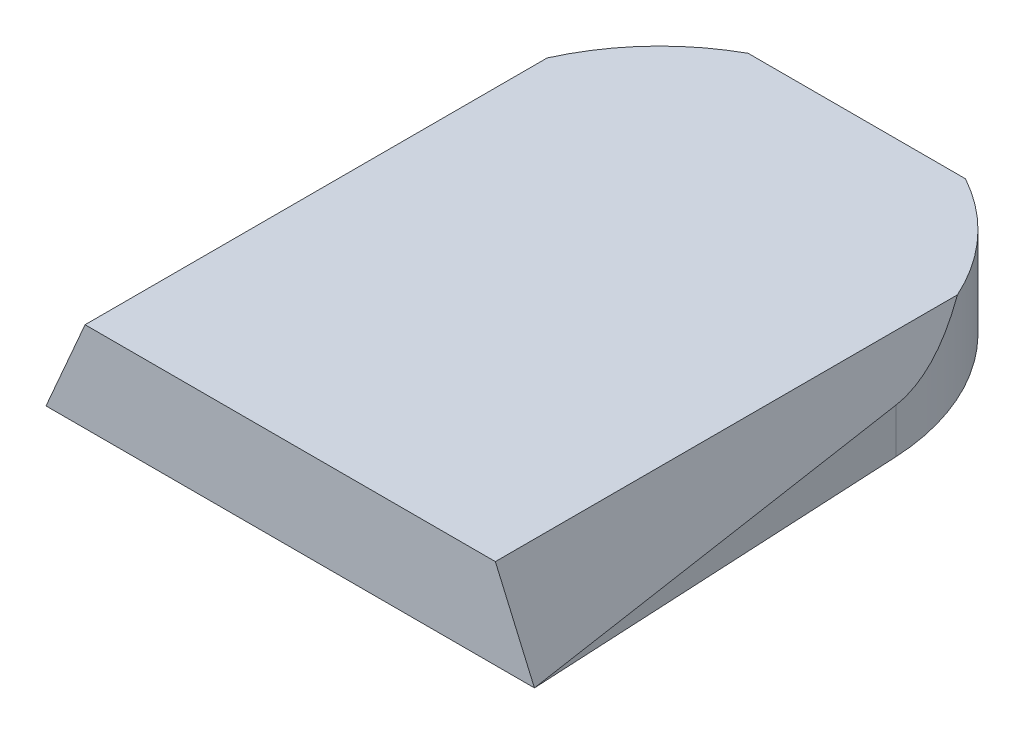
SolidWorks part; units mm, degrees
ref_plane "前视基准面" through (0, 0, 0) normal (0, 0, 1) x (1, 0, 0)
ref_plane "上视基准面" through (0, 0, 0) normal (0, 1, 0) x (1, 0, 0)
ref_plane "右视基准面" through (0, 0, 0) normal (1, 0, 0) x (0, 0, -1)
sketch "草图1" plane through (0, 0, 0) normal (0, 1, 0) x (1, 0, 0)
  line L0 (-10.9256, 0) -> (14.0744, 0)
  line L1 (-10.9256, 0) -> (14.0744, 0)
  line L2 (-3.9874, 29) -> (7.1363, 29)
  line L3 (1.5744, 0) -> (1.5744, 23.4999) construction
  line L4 (-9.9298, 19.4999) -> (-10.9256, 0)
  line L5 (13.0787, 19.4999) -> (14.0744, 0)
  line L6 (-9.7256, 23.4999) -> (-9.7256, 19.4999) construction
  arc A0 (-9.9298, 19.4999) -> (-3.9874, 29) centre (1.5744, 18.9124) cw
  arc A1 (7.1363, 29) -> (13.0787, 19.4999) centre (1.5744, 18.9124) cw
  point P3 (1.5744, 29)
  point P8 (1.5744, 0)
  point P12 (-9.9298, 19.4999)
  point P15 (13.0787, 19.4999)
  dimension "D1" = 25
  dimension "D2" = 29
  dimension "D4" = 90
  dimension "D5" = 0
  dimension "D8" = 4
extrude "凸台-拉伸1" add sketch "草图1" along normal blind 4.6
sketch "草图6" plane through (0, 0, 0) normal (0, 0, 1) x (1, 0, 0)
  line L0 (-10.9256, 0) -> (-8.9256, 4.6)
  line L1 (-10.9256, 4.6) -> (14.0744, 4.6) construction
  line L2 (-8.9256, 4.6) -> (-10.9256, 4.6)
  line L3 (-10.9256, 4.6) -> (-10.9256, 0)
  line L4 (1.5744, 0) -> (1.5744, 8.5759) construction
  line L5 (-10.9256, 0) -> (14.0744, 0) construction
  line L6 (12.0744, 4.6) -> (14.0744, 4.6)
  line L7 (14.0744, 0) -> (12.0744, 4.6)
  line L8 (14.0744, 4.6) -> (14.0744, 0)
  dimension "D1" = 21
extrude "切除-拉伸1" cut sketch "草图6" against normal through all
